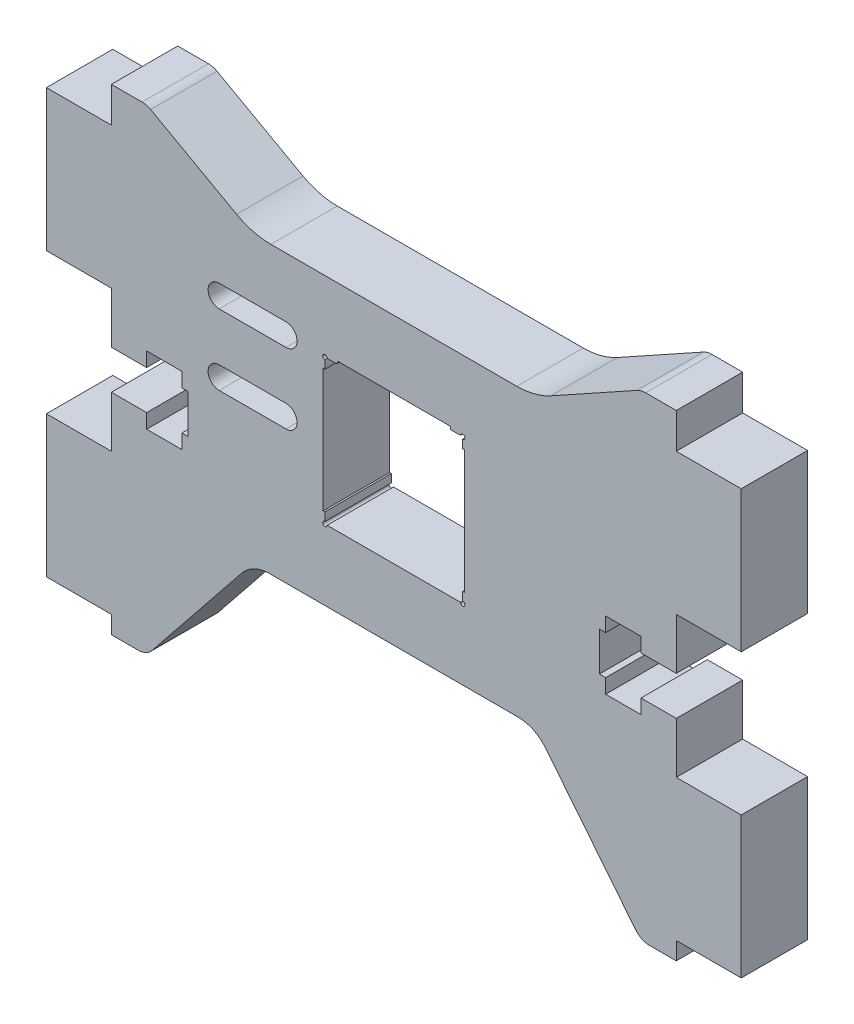
SolidWorks part; units mm, degrees
ref_plane "Front Plane" through (0, 0, 0) normal (0, 0, 1) x (1, 0, 0)
ref_plane "Top Plane" through (0, 0, 0) normal (0, 1, 0) x (1, 0, 0)
ref_plane "Right Plane" through (0, 0, 0) normal (1, 0, 0) x (0, 0, -1)
sketch "Sketch1" plane through (0, 0, 0) normal (0, 0, 1) x (1, 0, 0)
  line L0 (0, 0) -> (0, -23.137) construction
  line L1 (6.1952, -6.5) -> (-6.1952, -6.5)
  line L2 (6.1952, -6.5) -> (6.1952, 6.5)
  line L3 (6.1952, 6.5) -> (-6.1952, 6.5)
  line L4 (-6.1952, -6.5) -> (-6.1952, 6.5)
  line L5 (6.1952, -6.5) -> (-6.1952, 6.5) construction
  line L6 (6.1952, 6.5) -> (-6.1952, -6.5) construction
  line L7 (25.4, -23.137) -> (-25.4, -23.137) construction
  line L8 (25.4, 2.263) -> (25.4, -10.437)
  line L9 (25.4, -23.137) -> (31.242, -23.137)
  line L10 (-31.242, 2.263) -> (-25.4, 2.263)
  line L11 (31.242, -10.437) -> (25.4, -10.437)
  line L12 (31.242, -23.137) -> (31.242, -10.437)
  line L13 (25.4, -23.137) -> (25.4, -24.7245)
  line L14 (-12.7, -12.85) -> (12.7, -12.85)
  line L15 (12.7, -12.85) -> (22.225, -24.7245)
  line L16 (22.225, -24.7245) -> (25.4, -24.7245)
  line L17 (-12.7, 12.85) -> (12.7, 12.85)
  line L18 (-12.7, 12.85) -> (-22.225, 18.138)
  line L19 (-31.242, -10.437) -> (-25.4, -10.437)
  line L20 (-31.242, -23.137) -> (-31.242, -10.437)
  line L21 (-25.4, -23.137) -> (-31.242, -23.137)
  line L22 (-25.4, -23.137) -> (-25.4, -24.7245)
  line L23 (-22.225, -24.7245) -> (-25.4, -24.7245)
  line L24 (-12.7, -12.85) -> (-22.225, -24.7245)
  line L25 (-25.4, 18.138) -> (-22.225, 18.138)
  line L26 (-25.4, 2.263) -> (-25.4, -10.437)
  line L27 (31.242, 2.263) -> (25.4, 2.263)
  line L28 (31.242, 2.263) -> (31.242, 14.963)
  line L29 (31.242, 14.963) -> (25.4, 14.963)
  line L30 (25.4, 14.963) -> (25.4, 18.138)
  line L31 (25.4, 18.138) -> (22.225, 18.138)
  line L32 (-25.4, 14.963) -> (-25.4, 18.138)
  line L33 (12.7, 12.85) -> (22.225, 18.138)
  line L34 (-31.242, 14.963) -> (-25.4, 14.963)
  line L35 (-31.242, 2.263) -> (-31.242, 14.963)
  point P0 (0, 0)
  point P11 (0, -23.137)
  point P28 (0, -12.85)
  point P29 (0, 12.85)
  dimension "D1" = 13
  dimension "D2" = 12.3904
  dimension "D3" = 16.637
  dimension "D4" = 50.8
  dimension "D5" = 12.7
  dimension "D6" = 5.842
  dimension "D7" = 12.7
  dimension "D8" = 1.5875
  dimension "D9" = 12.7
  dimension "D10" = 6.35
  dimension "D11" = 3.175
  dimension "D12" = 6.35
  dimension "D13" = 12.7
  dimension "D16" = 12.7
  dimension "D17" = 3.175
  dimension "D18" = 3.175
extrude "Boss-Extrude1" add sketch "Sketch1" along normal blind 5.969
sketch "Sketch2" plane through (0, 0, 5.969) normal (0, 0, 1) x (1, 0, 0)
  line L0 (-25.4, -4.087) -> (25.4, -4.087) construction
  line L1 (-25.4, 2.263) -> (-25.4, -10.437) construction
  line L2 (25.4, -10.437) -> (25.4, 2.263) construction
  line L3 (22.225, -2.3344) -> (22.225, -1.039)
  line L4 (22.225, -5.8396) -> (25.4, -5.8396)
  line L5 (0, -4.087) -> (0, -12.85) construction
  line L6 (22.225, -2.3344) -> (25.4, -2.3344)
  line L7 (25.4, -5.8396) -> (25.4, -2.3344)
  line L8 (22.225, -5.8396) -> (25.4, -2.3344) construction
  line L9 (22.225, -2.3344) -> (25.4, -5.8396) construction
  line L10 (19.05, -7.135) -> (22.225, -7.135)
  line L11 (19.05, -7.135) -> (19.05, -5.8396)
  line L12 (19.05, -1.039) -> (22.225, -1.039)
  line L13 (22.225, -7.135) -> (22.225, -5.8396)
  line L14 (19.05, -7.135) -> (22.225, -1.039) construction
  line L15 (19.05, -1.039) -> (22.225, -7.135) construction
  line L16 (18.492, -5.8396) -> (19.05, -5.8396)
  line L17 (18.492, -5.8396) -> (18.492, -2.3344)
  line L18 (18.492, -2.3344) -> (19.05, -2.3344)
  line L19 (-12.7, -12.85) -> (12.7, -12.85) construction
  line L20 (18.492, -5.8396) -> (19.05, -2.3344) construction
  line L21 (18.492, -2.3344) -> (19.05, -5.8396) construction
  line L22 (19.05, -2.3344) -> (19.05, -1.039)
  line L23 (-18.492, -2.3344) -> (-19.05, -5.8396) construction
  line L24 (-18.492, -5.8396) -> (-19.05, -2.3344) construction
  line L25 (-19.05, -1.039) -> (-22.225, -7.135) construction
  line L26 (-19.05, -7.135) -> (-22.225, -1.039) construction
  line L27 (-22.225, -2.3344) -> (-25.4, -5.8396) construction
  line L28 (-22.225, -5.8396) -> (-25.4, -2.3344) construction
  line L29 (-19.05, -2.3344) -> (-19.05, -1.039)
  line L30 (-18.492, -2.3344) -> (-19.05, -2.3344)
  line L31 (-18.492, -5.8396) -> (-18.492, -2.3344)
  line L32 (-18.492, -5.8396) -> (-19.05, -5.8396)
  line L33 (-22.225, -7.135) -> (-22.225, -5.8396)
  line L34 (-19.05, -1.039) -> (-22.225, -1.039)
  line L35 (-19.05, -7.135) -> (-19.05, -5.8396)
  line L36 (-19.05, -7.135) -> (-22.225, -7.135)
  line L37 (-25.4, -5.8396) -> (-25.4, -2.3344)
  line L38 (-22.225, -2.3344) -> (-25.4, -2.3344)
  line L39 (-22.225, -5.8396) -> (-25.4, -5.8396)
  line L40 (-22.225, -2.3344) -> (-22.225, -1.039)
  point P6 (23.8125, -4.087)
  point P11 (20.6375, -4.087)
  point P16 (18.771, -4.087)
  point P37 (-18.771, -4.087)
  point P38 (-20.6375, -4.087)
  point P39 (-23.8125, -4.087)
  dimension "D1" = 3.175
  dimension "D2" = 3.175
  dimension "D3" = 3.5052
  dimension "D4" = 6.096
  dimension "D5" = 0.558
extrude "Cut-Extrude1" cut sketch "Sketch2" against normal through all
sketch "Sketch3" plane through (0, 0, 5.969) normal (0, 0, 1) x (1, 0, 0)
  line L0 (-6.1952, 0) -> (6.1952, 0) construction
  line L1 (-6.1952, 6.5) -> (-6.1952, -6.5) construction
  line L2 (6.1952, -6.5) -> (6.1952, 6.5) construction
  circle A0 centre (6.1952, 6.5) radius 0.1984
  circle A1 centre (-6.1952, 6.5) radius 0.1984
  circle A2 centre (-6.1952, -6.5) radius 0.1984
  circle A3 centre (6.1952, -6.5) radius 0.1984
  dimension "D1" = 0.3969
  dimension "D2" = 0.3969
extrude "Cut-Extrude2" cut sketch "Sketch3" against normal through all
fillet "Fillet1" radius 3.175 2 edges at (-12.7, -12.85, 2.9845) (12.7, -12.85, 2.9845)
fillet "Fillet2" radius 1.5875 4 edges at (22.225, -24.7245, 2.9845) (-22.225, -24.7245, 2.9845) (-22.225, 18.138, 2.9845) (22.225, 18.138, 2.9845)
sketch "Sketch4" plane through (0, 0, 5.969) normal (0, 0, 1) x (1, 0, 0)
  line L0 (-6.1952, 0) -> (6.1952, 0) construction
  line L1 (-6.1952, 6.3016) -> (-6.1952, -6.3016) construction
  line L2 (6.1952, -6.3016) -> (6.1952, 6.3016) construction
  line L4 (6.35, -5.5562) -> (-6.35, -5.5563)
  line L5 (6.35, -5.5562) -> (6.35, 5.5563)
  line L6 (6.35, 5.5563) -> (-6.35, 5.5562)
  line L7 (-6.35, -5.5563) -> (-6.35, 5.5562)
  line L8 (6.35, -5.5562) -> (-6.35, 5.5562) construction
  line L9 (6.35, 5.5563) -> (-6.35, -5.5563) construction
  point P6 (0, 0)
  dimension "D1" = 12.7
  dimension "D2" = 11.1125
extrude "Cut-Extrude3" cut sketch "Sketch4" against normal through all
sketch "Sketch5" plane through (0, 0, 5.969) normal (0, 0, 1) x (1, 0, 0)
  line L0 (5.9968, 6.5) -> (-5.9968, 6.5) construction
  line L1 (5.08, 6.25) -> (-5.08, 6.25)
  line L2 (5.08, 6.25) -> (5.08, 6.75)
  line L3 (5.08, 6.75) -> (-5.08, 6.75)
  line L4 (-5.08, 6.25) -> (-5.08, 6.75)
  line L5 (5.08, 6.25) -> (-5.08, 6.75) construction
  line L6 (5.08, 6.75) -> (-5.08, 6.25) construction
  point P0 (0, 6.5)
  dimension "D1" = 10.16
  dimension "D2" = 0.5
extrude "Cut-Extrude4" cut sketch "Sketch5" against normal through all
fillet "Fillet8" radius 0.1 4 edges at (5.08, 6.75, 2.9845) (5.08, 6.5, 2.9845) (-5.08, 6.75, 2.9845) (-5.08, 6.5, 2.9845)
sketch "Sketch6" plane through (0, 0, 5.969) normal (0, 0, 1) x (1, 0, 0)
  line L0 (-12.7, 12.85) -> (-12.7, -12.85) construction
  line L1 (12.7, 12.85) -> (-12.7, 12.85) construction
  line L2 (-11.1766, -12.85) -> (11.1766, -12.85) construction
  line L3 (-15.7, 6.5) -> (-9.7, 6.5) construction
  line L4 (-15.7, 7.5) -> (-9.7, 7.5)
  line L5 (-15.7, 5.5) -> (-9.7, 5.5)
  line L6 (-15.7, 0.15) -> (-9.7, 0.15) construction
  line L7 (-15.7, 1.15) -> (-9.7, 1.15)
  line L8 (-15.7, -0.85) -> (-9.7, -0.85)
  arc A0 (-15.7, 7.5) -> (-15.7, 5.5) centre (-15.7, 6.5) ccw
  arc A1 (-9.7, 5.5) -> (-9.7, 7.5) centre (-9.7, 6.5) ccw
  arc A2 (-15.7, 1.15) -> (-15.7, -0.85) centre (-15.7, 0.15) ccw
  arc A3 (-9.7, -0.85) -> (-9.7, 1.15) centre (-9.7, 0.15) ccw
  point P8 (-12.7, 6.5)
  point P17 (-12.7, 0.15)
  point P18 (-12.7, -2.413)
  dimension "D2" = 1
  dimension "D1" = 6
  dimension "D3" = 12.7
  dimension "D5" = 6.35
extrude "Cut-Extrude5" cut sketch "Sketch6" against normal through all
fillet "Fillet9" radius 6.35 2 edges at (12.7, 12.85, 2.9845) (-12.7, 12.85, 2.9845)
